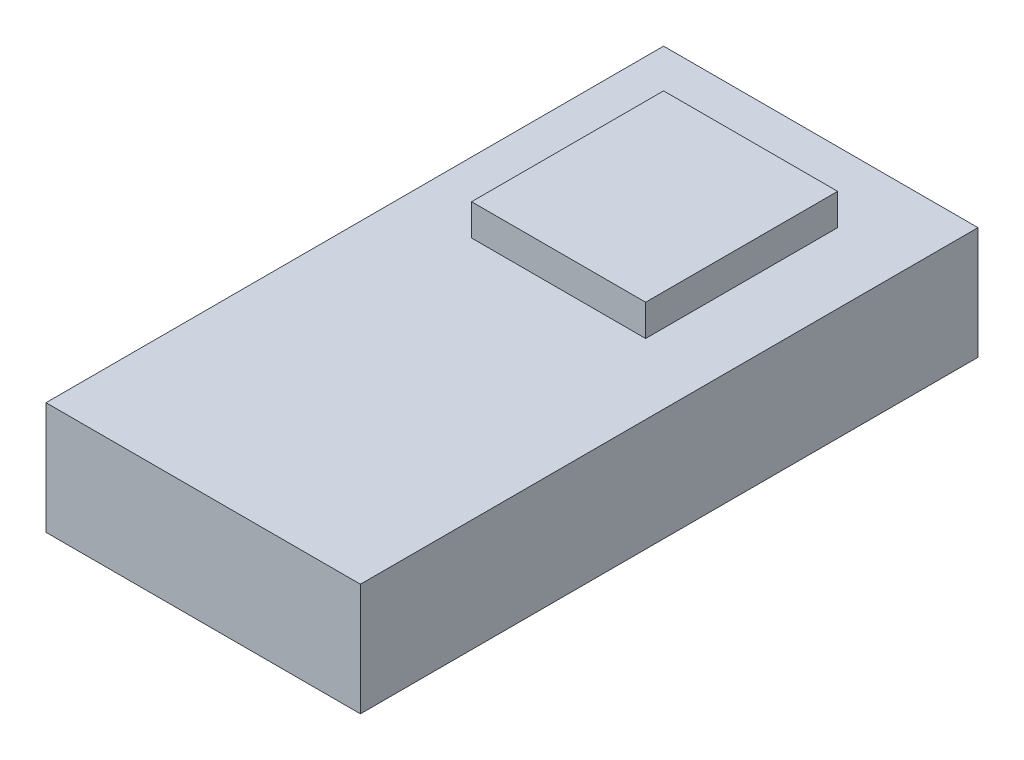
SolidWorks part; units mm, degrees
ref_plane "Front Plane" through (0, 0, 0) normal (0, 0, 1) x (1, 0, 0)
ref_plane "Top Plane" through (0, 0, 0) normal (0, 1, 0) x (1, 0, 0)
ref_plane "Right Plane" through (0, 0, 0) normal (1, 0, 0) x (0, 0, -1)
sketch "Sketch2" plane through (0, 0, 0) normal (0, 1, 0) x (1, 0, 0)
  line L1 (0, 0) -> (28, 0)
  line L2 (0, 0) -> (0, 55)
  line L3 (0, 55) -> (28, 55)
  line L4 (28, 0) -> (28, 55)
extrude "Boss-Extrude1" add sketch "Sketch2" along normal blind 10
sketch "Sketch3" plane through (0, 10, 0) normal (0, 1, 0) x (1, 0, 0)
  line L0 (0, 55) -> (0, 0) construction
  line L1 (6.25, 48.75) -> (21.75, 48.75)
  line L2 (6.25, 48.75) -> (6.25, 31.65)
  line L3 (6.25, 31.65) -> (21.75, 31.65)
  line L4 (21.75, 48.75) -> (21.75, 31.65)
  line L5 (28, 55) -> (0, 55) construction
  dimension "D1" = 6.25
  dimension "D2" = 15.5
  dimension "D3" = 17.1
  dimension "D4" = 6.25
extrude "Boss-Extrude2" add sketch "Sketch3" along normal blind 2.8
sketch "Sketch4" plane through (0, 10, 0) normal (0, 1, 0) x (1, 0, 0)
  text T0 "ESP32\r\n"
